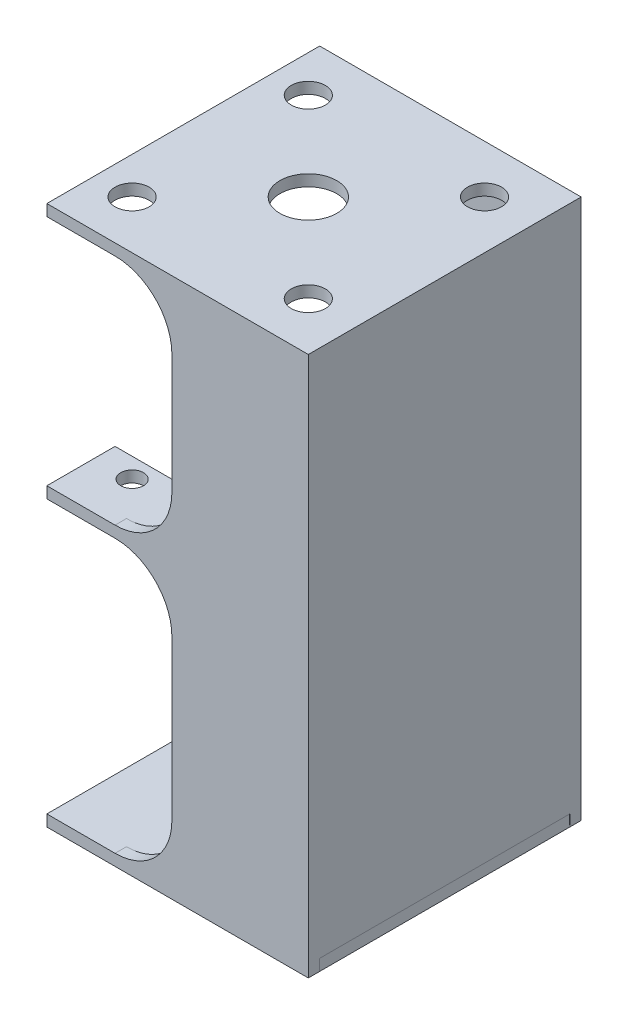
SolidWorks part; units mm, degrees
ref_plane "Front Plane" through (0, 0, 0) normal (0, 0, 1) x (1, 0, 0)
ref_plane "Top Plane" through (0, 0, 0) normal (0, 1, 0) x (1, 0, 0)
ref_plane "Right Plane" through (0, 0, 0) normal (1, 0, 0) x (0, 0, -1)
sketch "Sketch1" plane through (0, 0, 0) normal (0, 0, 1) x (1, 0, 0)
  line L0 (-0.9579, -45.5) -> (-45, -45.5)
  line L1 (-1, 47.5) -> (1, 47.5)
  line L2 (-1, 45.5) -> (-1, 4.5)
  line L3 (-1, -47.5) -> (1, -47.5)
  line L4 (1, 47.5) -> (1, -47.5)
  line L7 (1, -47.5) -> (-45, -47.5)
  line L8 (1, -47.5) -> (1, -45.5)
  line L9 (1, -45.5) -> (0.9579, -45.5)
  line L10 (-45, -47.5) -> (-45, -45.5)
  line L11 (1, 47.5) -> (-45, 47.5)
  line L12 (-1, 2.5) -> (-45, 2.5)
  line L13 (1, 2.5) -> (1, 4.5)
  line L14 (-1, 4.5) -> (-45, 4.5)
  line L15 (-45, 2.5) -> (-45, 4.5)
  line L16 (1, 47.5) -> (1, 45.5)
  line L17 (-1, 45.5) -> (-45, 45.5)
  line L18 (-45, 47.5) -> (-45, 45.5)
  line L19 (-1, 2.5) -> (-1, -45.5)
  line L20 (0.9579, -45.5) -> (1, -47.5) construction
  point P0 (0, 0)
extrude "Boss-Extrude1" add sketch "Sketch1" against normal blind 48
sketch "Sketch5" plane through (0, 47.5, 0) normal (0, 1, 0) x (1, 0, 0)
  line L1 (-45, 48) -> (-45, 0) construction
  line L5 (-45, 46) -> (-45, 2)
  circle A0 centre (-23, 24) radius 5
  circle A1 centre (-38.5, 39.5) radius 3
  circle A2 centre (-7.5, 39.5) radius 3
  circle A3 centre (-7.5, 8.5) radius 3
  circle A4 centre (-38.5, 8.5) radius 3
extrude "Cut-Extrude1" cut sketch "Sketch5" against normal up to next and the other way through all contours A0 | A1 | A2 | A3 | A4
sketch "Sketch10" plane through (0, 4.5, 0) normal (0, 1, 0) x (1, 0, 0)
  circle A0 centre (-23, 24) radius 12
  circle A1 centre (-7.5, 39.5) radius 2
  circle A2 centre (-7.5, 8.5) radius 2
  circle A3 centre (-38.5, 8.5) radius 2
  circle A4 centre (-38.5, 39.5) radius 2
extrude "Cut-Extrude3" cut sketch "Sketch10" against normal blind 2
sketch "Sketch15" plane through (0, 4.5, 0) normal (0, 1, 0) x (1, 0, 0)
  line L0 (-45, 48) -> (-45, 0) construction
  line L1 (-23, 36) -> (-45, 36)
  line L2 (-23, 36) -> (-23, 12)
  line L3 (-23, 12) -> (-45, 12)
  line L4 (-45, 36) -> (-45, 12)
extrude "Cut-Extrude5" cut sketch "Sketch15" against normal blind 2
sketch "Sketch16" plane through (0, -45.5, 0) normal (0, 1, 0) x (1, 0, 0)
  line L1 (1, 0) -> (-23, 0)
  line L2 (1, 0) -> (1, 2)
  line L3 (1, 2) -> (-23, 2)
  line L4 (-23, 0) -> (-23, 2)
  line L5 (1, 48) -> (-23, 48)
  line L6 (1, 48) -> (1, 46)
  line L7 (1, 46) -> (-23, 46)
  line L8 (-23, 48) -> (-23, 46)
extrude "Boss-Extrude7" add sketch "Sketch16" along normal blind 93 and the other way blind 2
fillet "Fillet1" radius 10 8 edges at (-23, 45.5, -1) (-23, 45.5, -47) (-23, 4.5, -47) (-23, 4.5, -1) (-23, 2.5, -1) (-23, 2.5, -47) (-23, -45.5, -47) (-23, -45.5, -1)
